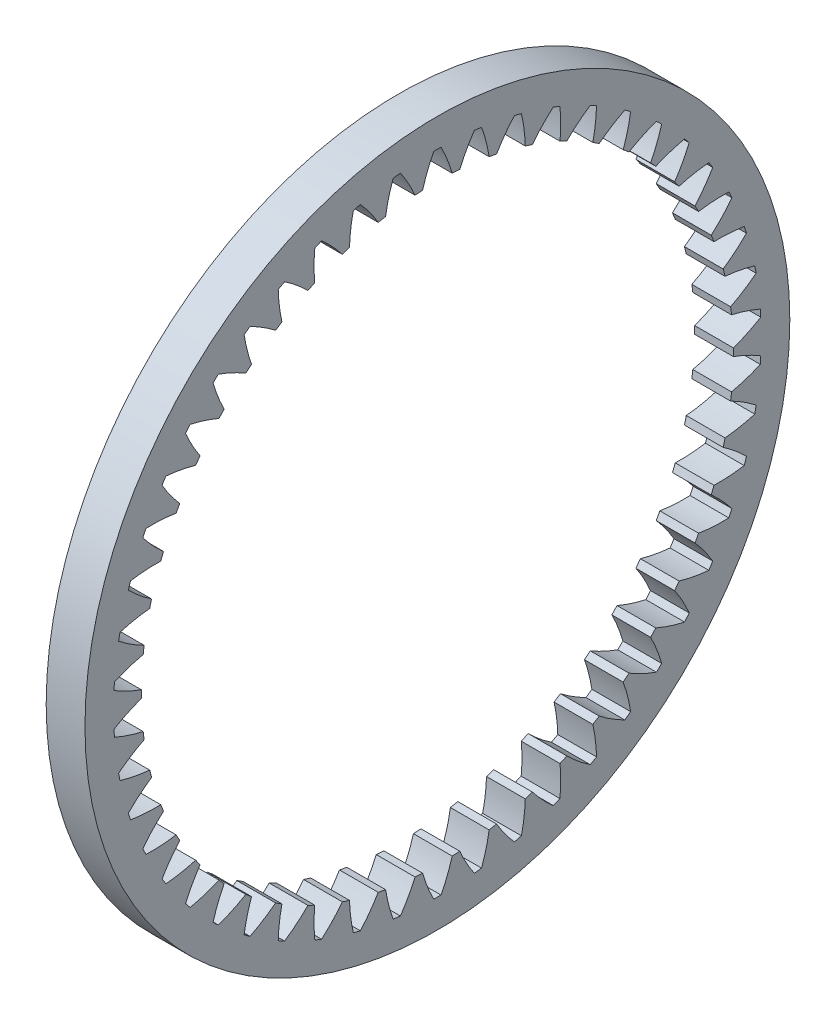
SolidWorks part; units mm, degrees
ref_plane "Plane1" through (0, 0, 0) normal (0, 0, 1) x (1, 0, 0)
ref_plane "Plane2" through (0, 0, 0) normal (0, 1, 0) x (1, 0, 0)
ref_plane "Plane3" through (0, 0, 0) normal (1, 0, 0) x (0, 0, -1)
other "Configuration Table"
sketch "HoldingSke" plane through (0, 0, 0) normal (0, 1, 0) x (1, 0, 0)
  line L0 (0, 0) -> (0.3673, -0.4377)
  line L1 (-15, 0) -> (100, 0) construction
  line L2 (0, 0) -> (-2.1039, 2.3779)
  line L3 (0, 0) -> (-11.863, 4.5341)
  line L4 (0, 0) -> (5.5511, 6.6156)
  line L5 (0, 0) -> (-23.7986, -8.8762)
  line L6 (0, 0) -> (-10.5278, -7.1032)
  line L7 (-2.1039, 2.3779) -> (3.3635, 27.1825)
  line L8 (-76.2, 4.1279) -> (-54.61, 4.1279)
  line L9 (-71.009, 38.7566) -> (-53.1078, 45.2721)
  line L10 (-76.2, 71.12) -> (104.1128, 71.12)
  line L11 (0, 0) -> (-5.5, 0)
  line L12 (-76.2, 101.6) -> (-76.147, 101.6)
  line L13 (24.9733, 27.94) -> (52.9518, 28.4284)
  line L14 (24.9733, 27.94) -> (24.9743, 27.94)
  line L15 (24.9733, 27.94) -> (100.4006, 29.5858)
  circle A0 centre (0, 0) radius 50
  circle A1 centre (0, 0) radius 12.7
  circle A2 centre (0, 0) radius 12.7
  dimension "MHD" = 25.4
  dimension "Hub_dia" = 25.4
  dimension "Diameter" = 100
  dimension "Num_teeth" = 50
  dimension "Pitch" = 0.5714
  dimension "Overall_len" = 25.4
  dimension "Show_teeth" = 50
  dimension "Thickness" = 12.7
  dimension "OAL" = 25.4001
  dimension "T_dim" = 21.59
  dimension "Ap" = 20
  dimension "H" = 19.05
  dimension "Pitch_radius" = 180.3128
  dimension "Width" = 5.5
  dimension "Backlash" = 0.053
  dimension "Addendum_fac" = 1
  dimension "Dedendum_fac" = 1.25
  dimension "Clearance_fac" = 0.25
  dimension "Dedendum_add" = 0.001
  dimension "Module" = 1.75
sketch "BasProSke" plane through (0, 0, 0) normal (0, 1, 0) x (1, 0, 0)
  line L0 (-10, 0) -> (60, 0) construction
  line L1 (0, 42) -> (0, 50)
  line L2 (0, 42) -> (5.5, 42)
  line L3 (5.5, 42) -> (5.5, 50)
  line L4 (5.5, 50) -> (0, 50)
  dimension "Diameter" = 100
  dimension "Thickness" = 5.5
  dimension "Inside_diameter" = 84
revolve "Base-Revolve" add sketch "BasProSke" angle 360 about L0
sketch "TooCutSke" plane through (0, 0, 0) normal (1, 0, 0) x (0, 0, -1)
  line L3 (1.5067, 43.724) -> (1.5067, 53.6633) construction
  line L4 (0, 0) -> (0, 59.563) construction
  line L5 (0, 0) -> (-4.2903, 68.1927) construction
  line L6 (-18.9149, 35.8835) -> (35.4449, 39.3036) construction
  circle A0 centre (0, 0) radius 43.75 construction
  circle A1 centre (0, 0) radius 45.9385 construction
  circle A2 centre (0, 0) radius 37.0004 construction
  circle A3 centre (0, 0) radius 41.9746 construction
  arc A4 (2.1103, 41.9215) -> (0.5137, 45.9356) centre (-18.9149, 35.8835) ccw
  arc A5 (2.1103, 41.9215) -> (-2.1103, 41.9215) centre (0, 0) ccw
  arc A6 (0.5137, 45.9356) -> (-0.5137, 45.9356) centre (0, 0) ccw
  arc A7 (-0.5137, 45.9356) -> (-2.1103, 41.9215) centre (18.9149, 35.8835) ccw
  dimension "Pitch_dia" = 87.5
  dimension "Base_dia" = 74.0008
  dimension "Root_dia" = 91.877
  dimension "Overcut_dia" = 83.9492
  dimension "Flank_rad" = 21.875
  dimension "Half_ang" = 3.6
  dimension "Half_CT" = 1.5067
extrude "ToothCut" cut sketch "TooCutSke" along normal through all
fillet "Breaks" [suppressed] radius 0.175
fillet "RootFillets" [suppressed] radius 0.4385
pattern_circular "TeethCuts" count 50 every 7.2 about axis through (-10, 0, 0) along (1, 0, 0) of "RootFillets", "Breaks", "ToothCut"
equation "' \"Module@HoldingSke\" = 6.35"
equation "' \"Num_teeth@HoldingSke\" = 24"
equation "' \"Ap@HoldingSke\" =  14.5"
equation "' \"Ap@HoldingSke\" = 14.5"
equation "' \"Width@HoldingSke\" = 12"
equation "' \"Diameter@HoldingSke\" = 8 * 25.4"
equation "' \"Show_teeth@HoldingSke\" = 100"
equation "' \"Backlash@HoldingSke\" = 0.009 * 25.4"
equation "' \"Addendum_fac@HoldingSke\" = 1.0"
equation "' \"Dedendum_fac@HoldingSke\" = 1.25"
equation "' \"Dedendum_add@HoldingSke\" = 0.00005 * 25.4"
equation "' \"Clearance_fac@HoldingSke\" = 0.25"
equation "\"Pitch@HoldingSke\" = 1 / \"Module@HoldingSke\" "
equation "\"Overcut_dia@TooCutSke\" = (\"Num_teeth@HoldingSke\" - 2 * \"Addendum_fac@HoldingSke\") / \"Pitch@HoldingSke\" - 0.002 * 25.4"
equation "\"Pitch_dia@TooCutSke\" = \"Num_teeth@HoldingSke\" / \"Pitch@HoldingSke\""
equation "\"Base_dia@TooCutSke\" = \"Num_teeth@HoldingSke\" / \"Pitch@HoldingSke\" * cos((\"Ap@HoldingSke\"  * 3.14159265 / 180)) * 0.90"
equation "\"Root_dia@TooCutSke\" = \"Num_teeth@HoldingSke\"  / \"Pitch@HoldingSke\" + 2 *  \"Dedendum_fac@HoldingSke\"/ \"Pitch@HoldingSke\" + \"Dedendum_add@HoldingSke\" * 2"
equation "\"Half_ang@TooCutSke\" = 180 / \"Num_teeth@HoldingSke\""
equation "\"Half_CT@TooCutSke\" = \"Num_teeth@HoldingSke\" / \"Pitch@HoldingSke\" * sin((3.14159265 / 2 / \"Num_teeth@HoldingSke\")) / 2 + 10 * \"Backlash@HoldingSke\" / 4"
equation "\"Flank_rad@TooCutSke\" = \"Num_teeth@HoldingSke\" / \"Pitch@HoldingSke\" / 4"
equation "\"Radius@RootFillets\"= \"Clearance_fac@HoldingSke\" / \"Pitch@HoldingSke\" + \"Dedendum_add@HoldingSke\""
equation "\"Break_rad@Breaks\" = 0.02 / \"Pitch@HoldingSke\" * 5"
equation "\"Num_teeth@TeethCuts\" = int( \"Show_teeth@HoldingSke\" ) + 1"
equation "\"Num_teeth@TeethCuts\" = ((sgn( \"Num_teeth@TeethCuts\" - \"Num_teeth@HoldingSke\" )-1)*( \"Num_teeth@TeethCuts\" - \"Num_teeth@HoldingSke\" ))/-2+ \"Num_teeth@HoldingSke\""
equation "\"Num_teeth@TeethCuts\" = ((sgn( \"Num_teeth@TeethCuts\" - 2.0)+1)*( \"Num_teeth@TeethCuts\" - 2.0))/2 +2.0"
equation "\"Angle@TeethCuts\" = 360.0 / \"Num_teeth@HoldingSke\""
equation "\"Diameter@BasProSke\" = \"Num_teeth@HoldingSke\"  / \"Pitch@HoldingSke\" + 2 *  \"Dedendum_fac@HoldingSke\"/ \"Pitch@HoldingSke\" + \"Dedendum_add@HoldingSke\" * 2 + 0.002 * 25.4"
equation "\"Diameter@BasProSke\" = ((sgn( \"Diameter@BasProSke\"  - \"Diameter@HoldingSke\" )+1)*( \"Diameter@BasProSke\"  - \"Diameter@HoldingSke\" ))/2 + \"Diameter@HoldingSke\""
equation "\"Inside_diameter@BasProSke\" =  (\"Num_teeth@HoldingSke\" - 2 * \"Addendum_fac@HoldingSke\") / \"Pitch@HoldingSke\" "
equation "\"Thickness@BasProSke\"  = \"Width@HoldingSke\""
